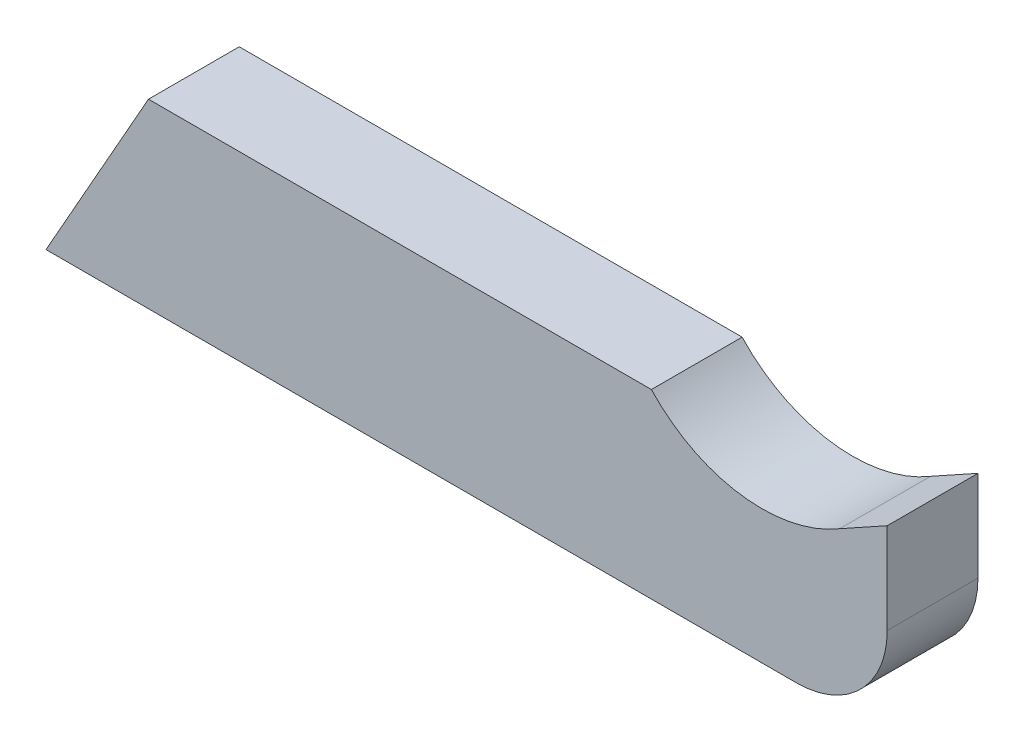
SolidWorks part; units mm, degrees
ref_plane "Front Plane" through (0, 0, 0) normal (1, 0, 0) x (0, 1, 0)
ref_plane "Top Plane" through (0, 0, 0) normal (0, 0, 1) x (0, 1, 0)
ref_plane "Right Plane" through (0, 0, 0) normal (0, 1, 0) x (-1, 0, 0)
sketch "Sketch1" plane through (0, 0, 0) normal (0, 0, 1) x (0, 1, 0)
  line L0 (-2.1229, 14.2549) -> (-2.1229, -10.5533)
  line L1 (0.8771, -13.5533) -> (3.8771, -13.5533)
  line L2 (3.8771, -13.5533) -> (3.0064, -11.9839)
  line L3 (3.8771, -5.7568) -> (3.8771, 10.8675)
  line L4 (3.8771, 10.8675) -> (-2.1229, 14.2549)
  arc A0 (-2.1229, -10.5533) -> (0.8771, -13.5533) centre (0.8771, -10.5533) ccw
  arc A1 (3.8771, -5.7568) -> (3.0064, -11.9839) centre (7.2923, -9.4087) ccw
  dimension "D1" = 6
extrude "Boss-Extrude1" add sketch "Sketch1" along normal blind 3
